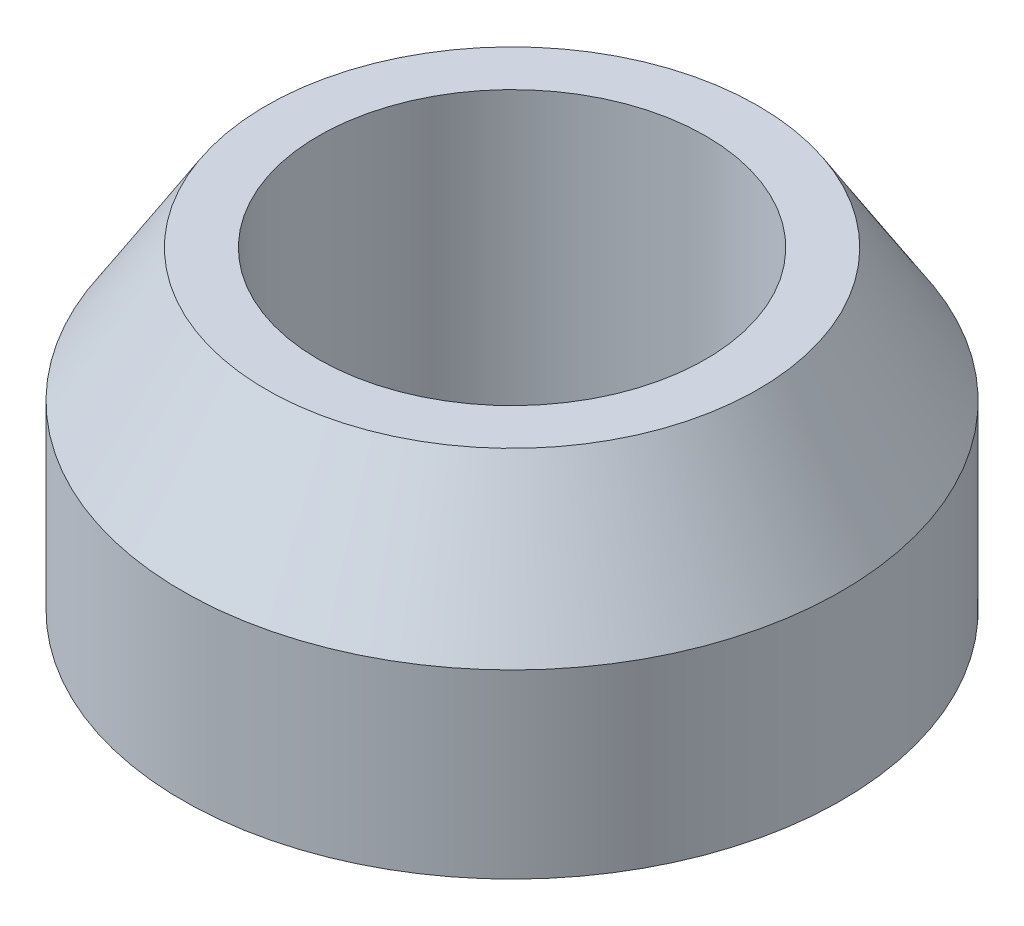
SolidWorks part; units mm, degrees
ref_plane "Front" through (0, 0, 0) normal (0, 0, 1) x (1, 0, 0)
ref_plane "Top" through (0, 0, 0) normal (0, 1, 0) x (1, 0, 0)
ref_plane "Right" through (0, 0, 0) normal (1, 0, 0) x (0, 0, -1)
sketch "Sketch1" plane through (0, 0, 0) normal (0, 0, 1) x (1, 0, 0)
  line L0 (0, 0) -> (0, 10969.9259) construction
  line L1 (3.15, 0) -> (3.15, 1.7311)
  line L3 (1.85, 3) -> (1.85, 0)
  line L4 (1.85, 0) -> (3.15, 0)
  line L5 (1.85, 3) -> (2.35, 3)
  line L6 (2.35, 3) -> (3.15, 1.7311)
  dimension "D1" = 3
  dimension "D2" = 6.3
  dimension "D3" = 1.3
  dimension "D4" = 1.5
  dimension "D5" = 0.5
revolve "Revolve1" add sketch "Sketch1" angle 360 about L0
